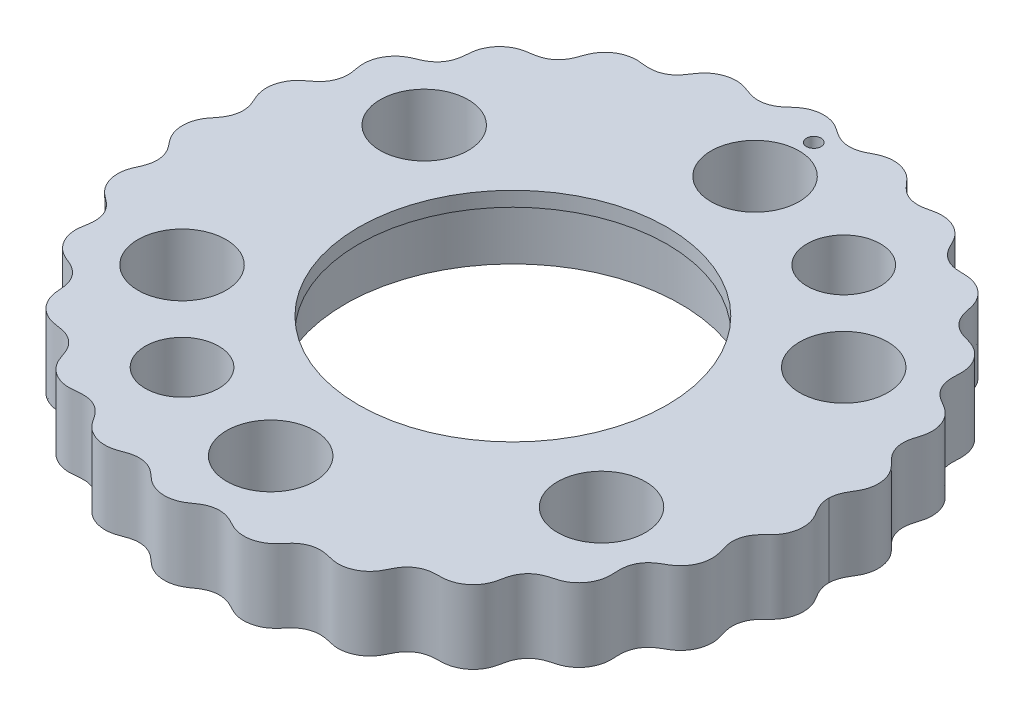
SolidWorks part; units mm, degrees
material "Like ABS"
ref_plane "Front Plane" through (0, 0, 0) normal (0, 0, 1) x (1, 0, 0)
ref_plane "Top Plane" through (0, 0, 0) normal (0, 1, 0) x (1, 0, 0)
ref_plane "Right Plane" through (0, 0, 0) normal (1, 0, 0) x (0, 0, -1)
sketch "Sketch1" plane through (0, 0, 0) normal (0, 1, 0) x (1, 0, 0)
  spline S0 degree 4 poles (18.6029, 11.2545) (18.6075, 11.136) (18.6309, 10.8996) (18.7179, 10.5625) (18.9374, 10.1618) (19.2203, 9.8531) (19.5263, 9.6277) (19.8338, 9.4559) (20.1167, 9.2925) (20.3955, 9.0753) (20.6516, 8.7949) (20.9212, 8.3592) (21.0701, 7.871) (21.0935, 7.3941) (21.0151, 6.9603) (20.9268, 6.6713) (20.827, 6.3532) (20.7583, 5.9932) (20.7579, 5.5953) (20.855, 5.178) (21.0326, 4.8178) (21.2602, 4.5208) (21.5076, 4.2761) (21.7427, 4.0542) (21.9657, 3.7863) (22.1537, 3.4641) (22.3225, 2.9952) (22.3687, 2.5028) (22.3031, 2.0452) (22.1511, 1.6464) (22.0285, 1.4194) (21.9119, 1.2324) (21.8067, 1.0573) (21.7163, 0.8934) (21.6305, 0.703) (21.5677, 0.5145) (21.5301, 0.3455) (21.5114, 0.2182) (21.5031, 0.1178) (21.4994, 0.0196) (21.5, -0.0455) (21.5057, -0.1633) (21.518, -0.2671) (21.5363, -0.3716) (21.5605, -0.4763) (21.5978, -0.6046) (21.6488, -0.7429) (21.7155, -0.8894) (21.7983, -1.0429) (21.8809, -1.1813) (21.9656, -1.3183) (22.0477, -1.4571) (22.1416, -1.6354) (22.2863, -1.9816) (22.3684, -2.421) (22.3358, -2.9349) (22.1741, -3.4197) (21.991, -3.7495) (21.772, -4.0233) (21.539, -4.2475) (21.2876, -4.4904) (21.0523, -4.786) (20.8663, -5.1459) (20.7615, -5.5648) (20.7557, -5.9689) (20.8225, -6.3389) (20.9266, -6.6708) (21.0208, -6.9784) (21.0782, -7.3225) (21.0775, -7.6978) (21.0031, -8.0938) (20.8436, -8.4925) (20.6233, -8.8316) (20.3625, -9.1053) (20.0808, -9.3156) (19.7984, -9.4746) (19.4941, -9.6484) (19.193, -9.8781) (18.9224, -10.185) (18.7166, -10.5727) (18.6147, -10.9677) (18.5925, -11.3426) (18.6115, -11.683) (18.6241, -11.9911) (18.5951, -12.3311) (18.5028, -12.6932) (18.3324, -13.0606) (18.0751, -13.4116) (17.7743, -13.6867) (17.4523, -13.8864) (17.126, -14.0192) (16.8121, -14.1026) (16.4734, -14.1962) (16.1245, -14.3457) (15.7808, -14.582) (15.4788, -14.9208) (15.2835, -15.2936) (15.1749, -15.6637) (15.1113, -15.9998) (15.0432, -16.2929) (14.9273, -16.6033) (14.7486, -16.9176) (14.4956, -17.2208) (14.1638, -17.4903) (13.8066, -17.6794) (13.4438, -17.7919) (13.0938, -17.8383) (12.7683, -17.8404) (12.4162, -17.8477) (12.0403, -17.9075) (11.6491, -18.0533) (11.2738, -18.3086) (10.994, -18.6222) (10.7986, -18.9537) (10.654, -19.2627) (10.5146, -19.5288) (10.3249, -19.7991) (10.0732, -20.058) (9.7528, -20.2872) (9.3635, -20.4656) (8.8909, -20.5765) (8.4239, -20.5773) (8.0011, -20.4727) (7.5788, -20.3726) (7.1982, -20.3396) (6.7831, -20.3853) (6.3568, -20.5422) (6.0096, -20.7778) (5.7397, -21.0508) (5.5235, -21.3136) (5.3222, -21.5355) (5.0709, -21.7488) (4.7631, -21.9354) (4.2941, -22.1159) (3.7831, -22.1727) (3.2971, -22.1042) (2.8667, -21.9331) (2.5797, -21.7766) (2.2654, -21.614) (1.9042, -21.4879) (1.4895, -21.4317) (1.0382, -21.4801) (0.6443, -21.6241) (0.3167, -21.822) (0.0427, -22.0226) (-0.2074, -22.1862) (-0.5976, -22.3746) (-1.0573, -22.4797) (-1.5638, -22.4712) (-2.0548, -22.3329) (-2.3972, -22.1622) (-2.6839, -21.9521) (-2.9229, -21.7281) (-3.1883, -21.4926) (-3.5084, -21.2816) (-3.8975, -21.126) (-4.347, -21.0633) (-4.7636, -21.107) (-5.1287, -21.2185) (-5.4432, -21.3443) (-5.7258, -21.4396) (-6.0477, -21.503) (-6.4056, -21.516) (-6.9028, -21.4457) (-7.3774, -21.2468) (-7.7696, -20.9496) (-8.0632, -20.5887) (-8.2391, -20.3115) (-8.4387, -20.0171) (-8.6983, -19.7336) (-9.0382, -19.4877) (-9.459, -19.3178) (-9.8732, -19.2589) (-10.2536, -19.2774) (-10.5887, -19.3211) (-10.8854, -19.3421) (-11.2121, -19.3225) (-11.5609, -19.2451) (-12.0244, -19.0522) (-12.4339, -18.7404) (-12.7391, -18.3536) (-12.9328, -17.9294) (-13.034, -17.6163) (-13.1553, -17.2811) (-13.3382, -16.9419) (-13.6084, -16.6204) (-13.9753, -16.3534) (-14.3622, -16.1956) (-14.7346, -16.1206) (-15.0692, -16.0797) (-15.3611, -16.0255) (-15.6715, -15.9244) (-15.9889, -15.7621) (-16.3889, -15.4591) (-16.707, -15.0543) (-16.9055, -14.6024) (-16.9861, -14.1422) (-17.0061, -13.8129) (-17.0516, -13.3486) (-17.2053, -12.8653) (-17.5221, -12.4221) (-17.9472, -12.11) (-18.2892, -11.9462) (-18.6023, -11.8239) (-18.8706, -11.6981) (-19.1448, -11.5225) (-19.4105, -11.2862) (-19.7169, -10.8984) (-19.9236, -10.4312) (-20.0056, -9.9443) (-19.9703, -9.4736) (-19.9036, -9.1351) (-19.8344, -8.6685) (-19.87, -8.1618) (-20.0706, -7.6597) (-20.4022, -7.2591) (-20.6929, -7.0172) (-20.9651, -6.8212) (-21.1925, -6.6324) (-21.4131, -6.3939) (-21.6103, -6.0991) (-21.8094, -5.647) (-21.8921, -5.1426) (-21.849, -4.6501) (-21.6959, -4.2025) (-21.5464, -3.8907) (-21.3642, -3.4543) (-21.2752, -2.9536) (-21.3478, -2.4176) (-21.5717, -1.9486) (-21.7936, -1.6436) (-22.008, -1.3867) (-22.1801, -1.1472) (-22.3332, -0.8616) (-22.4495, -0.5273) (-22.5298, -0.0326) (-22.4807, 0.4807) (-22.3113, 0.9462) (-22.0028, 1.4061) (-21.7069, 1.7352) (-21.4589, 2.1409) (-21.3173, 2.6263) (-21.2993, 3.0795) (-21.3816, 3.487) (-21.5215, 3.836) (-21.6648, 4.1376) (-21.7709, 4.412) (-21.8468, 4.7263) (-21.8752, 5.0782) (-21.8287, 5.5771) (-21.6522, 6.0617) (-21.3708, 6.4704) (-20.9554, 6.8384) (-20.5863, 7.0843) (-20.2459, 7.418) (-19.9902, 7.8549) (-19.8626, 8.2901) (-19.8431, 8.7048) (-19.8931, 9.0765) (-19.9566, 9.4036) (-19.99, 9.6951) (-19.9844, 10.0179) (-19.9234, 10.3644) (-19.7778, 10.7686) (-19.5075, 11.197) (-19.1432, 11.548) (-18.707, 11.7881) (-18.2921, 11.9415) (-17.9411, 12.1158) (-17.615, 12.3592) (-17.3407, 12.6771) (-17.1131, 13.113) (-16.9964, 13.6606) (-17.0054, 14.3306) (-16.7364, 15.0616) (-16.2913, 15.5744) (-15.7979, 15.8786) (-15.396, 16.016) (-15.1079, 16.0745) (-14.7772, 16.1149) (-14.408, 16.1828) (-14.0197, 16.33) (-13.6456, 16.5864) (-13.3098, 16.965) (-13.0983, 17.3919) (-12.9786, 17.8186) (-12.7567, 18.327) (-12.3913, 18.8027) (-11.8998, 19.1399) (-11.3468, 19.3098) (-10.9215, 19.3419) (-10.6278, 19.3257) (-10.3528, 19.2899) (-10.0923, 19.2689) (-9.79, 19.2729) (-9.4538, 19.3259) (-9.0826, 19.4637) (-8.6653, 19.7489) (-8.3568, 20.1103) (-8.1354, 20.4932) (-7.7931, 20.9281) (-7.4026, 21.2327) (-6.9296, 21.4377) (-6.4342, 21.5139) (-6.0801, 21.5062) (-5.761, 21.4486) (-5.4799, 21.3585) (-5.1691, 21.234) (-4.8101, 21.1175) (-4.2947, 21.0501) (-3.7627, 21.1476) (-3.3145, 21.3875) (-2.9563, 21.6957) (-2.706, 21.934) (-2.3276, 22.2175) (-1.8725, 22.4102) (-1.3673, 22.487) (-0.8758, 22.437) (-0.5342, 22.3403) (-0.2392, 22.2038) (0.0107, 22.0455) (0.2812, 21.8471) (0.6018, 21.6456) (1.0852, 21.4547) (1.7135, 21.4142) (2.2854, 21.5972) (2.7601, 21.8887) (3.2776, 22.0998) (3.7655, 22.1719) (4.2739, 22.1193) (4.7371, 21.9474) (5.0441, 21.7674) (5.2958, 21.5605) (5.4982, 21.3439) (5.7115, 21.0838) (5.9734, 20.8092) (6.402, 20.5019) (6.9217, 20.3384) (7.4286, 20.3423) (7.8839, 20.4428) (8.2031, 20.5253) (8.6655, 20.5905) (9.1564, 20.541) (9.6395, 20.3632) (10.0511, 20.076) (10.3034, 19.824) (10.4954, 19.5596) (10.637, 19.2985) (10.7794, 18.9927) (10.9663, 18.6617) (11.2365, 18.3428) (11.6043, 18.077) (11.9937, 17.92) (12.3726, 17.8514) (12.7287, 17.8398) (13.0575, 17.8402) (13.5204, 17.7867) (13.9824, 17.6156) (14.4052, 17.3223) (14.7317, 16.9409) (14.9129, 16.6326) (15.0323, 16.3277) (15.1038, 16.0387) (15.1659, 15.7063) (15.2662, 15.3387) (15.4509, 14.9631) (15.7431, 14.6159) (16.0823, 14.3692) (16.4321, 14.2105) (16.7735, 14.1119) (17.0913, 14.0302) (17.5249, 13.8621) (17.9284, 13.5808) (18.2639, 13.1907) (18.4841, 12.7394) (18.5822, 12.3946) (18.621, 12.0687) (18.6175, 11.7703) (18.595, 11.4321) (18.6023, 11.0501) (18.69, 10.6404) (18.8892, 10.2326) (19.1578, 9.9111) (19.4576, 9.6724) (19.7634, 9.4931) (20.0501, 9.335) (20.3381, 9.1271) (20.6059, 8.8542) (20.8888, 8.4298) (21.0532, 7.9505) (21.0949, 7.4807) (21.0358, 7.0511) (20.9572, 6.7626) (20.8511, 6.4397) (20.7645, 6.0666) (20.7498, 5.6474) (20.844, 5.2034) (21.0261, 4.8267) (21.2579, 4.5228) (21.5095, 4.2743) (21.7471, 4.0499) (21.9729, 3.7768) (22.1629, 3.446) (22.3301, 2.9643) (22.3688, 2.459) (22.2909, 1.993) (22.125, 1.5913) (21.9948, 1.3636) (21.8754, 1.1738) (21.7855, 1.0192) (21.7229, 0.9018) (21.6699, 0.7888) (21.6258, 0.6809) (21.5876, 0.571) (21.5558, 0.4582) (21.5339, 0.3595) (21.5196, 0.2744) (21.5104, 0.198) (21.5049, 0.135) (21.5, 0.0567) (21.4996, -0.0017) (21.5018, -0.1012) (21.5095, -0.1957) (21.52, -0.278) (21.5372, -0.3768) (21.5635, -0.4882) (21.5962, -0.5972) (21.6446, -0.7314) (21.7208, -0.903) (21.8329, -1.1074) (21.9824, -1.3413) (22.1279, -1.5977) (22.29, -1.9928) (22.3678, -2.4527) (22.3316, -2.9539) (22.1699, -3.4295) (21.9869, -3.7545) (21.7737, -4.0201) (21.5527, -4.235) (21.3073, -4.4702) (21.0701, -4.7589) (20.8765, -5.1175) (20.7635, -5.5432) (20.754, -5.9559) (20.8209, -6.3344) (20.9276, -6.6735) (21.0237, -6.9882) (21.08, -7.3402) (21.0755, -7.7242) (20.9743, -8.2226) (20.75, -8.681) (20.4407, -9.0464) (20.0199, -9.3618) (19.6438, -9.5512) (19.2696, -9.7988) (18.8657, -10.2421) (18.6796, -10.6464) (18.6183, -10.9774) (18.6053, -11.2049) knots 0 0 0 0 0 0.002701 0.005401 0.007852 0.010303 0.012162 0.01402 0.015879 0.017738 0.020183 0.022628 0.027478 0.029198 0.030919 0.032639 0.034359 0.036796 0.039233 0.041633 0.044032 0.045873 0.047715 0.049556 0.051397 0.053785 0.056173 0.060839 0.062515 0.06419 0.065866 0.066703 0.067541 0.06884 0.070138 0.071436 0.072085 0.072735 0.073159 0.073583 0.074192 0.074801 0.075411 0.07602 0.076629 0.077238 0.078456 0.079374 0.080292 0.08121 0.082128 0.083046 0.083964 0.0858 0.090659 0.093093 0.095528 0.097369 0.09921 0.101051 0.102892 0.105333 0.107775 0.110206 0.112638 0.114469 0.1163 0.118132 0.119963 0.122386 0.12481 0.12725 0.129691 0.131536 0.133381 0.135227 0.137072 0.139519 0.141967 0.144472 0.146978 0.148733 0.150488 0.152242 0.153997 0.156479 0.158961 0.161407 0.163853 0.165702 0.167552 0.169401 0.171251 0.173704 0.176158 0.178823 0.181488 0.183199 0.184911 0.186622 0.188334 0.190723 0.193111 0.195563 0.198015 0.199869 0.201722 0.203576 0.205429 0.207889 0.210349 0.213008 0.215667 0.217374 0.219082 0.220789 0.222496 0.224879 0.227262 0.22972 0.232177 0.235893 0.23775 0.239608 0.242074 0.244541 0.247193 0.249845 0.251549 0.253252 0.254955 0.256659 0.259036 0.261413 0.266339 0.268201 0.270063 0.271925 0.273787 0.276259 0.278732 0.281378 0.284024 0.285723 0.287422 0.289122 0.290821 0.295564 0.298032 0.300501 0.302367 0.304233 0.3061 0.307966 0.310444 0.312923 0.315563 0.318202 0.319898 0.321593 0.323288 0.324983 0.327349 0.329714 0.334663 0.336534 0.338404 0.340274 0.342144 0.344629 0.347114 0.349748 0.352381 0.354072 0.355763 0.357454 0.359146 0.361505 0.363865 0.368826 0.3707 0.372574 0.374449 0.376323 0.378814 0.381305 0.383932 0.386559 0.388246 0.389933 0.391621 0.393308 0.395662 0.398016 0.402988 0.404866 0.406745 0.408623 0.410502 0.415496 0.418117 0.420737 0.42242 0.424103 0.425787 0.42747 0.429818 0.432167 0.436982 0.438947 0.440912 0.442877 0.444842 0.449687 0.452301 0.454914 0.456594 0.458273 0.459953 0.461632 0.463975 0.466317 0.471143 0.473113 0.475082 0.477052 0.479021 0.483878 0.486485 0.489092 0.490767 0.492443 0.494118 0.495794 0.498131 0.500468 0.505475 0.507365 0.509256 0.513038 0.515553 0.518068 0.520669 0.523269 0.524941 0.526613 0.528284 0.529956 0.532287 0.534618 0.539637 0.541532 0.543426 0.547216 0.549737 0.552259 0.554853 0.557447 0.559114 0.560782 0.56245 0.564118 0.566443 0.568769 0.572172 0.575575 0.5778 0.580025 0.58225 0.584475 0.587001 0.589527 0.593322 0.597118 0.602145 0.606799 0.608468 0.610137 0.611805 0.613474 0.61607 0.618666 0.621185 0.623705 0.627493 0.629386 0.63128 0.636295 0.640961 0.642634 0.644306 0.645979 0.647652 0.648953 0.650254 0.652856 0.65537 0.657884 0.661663 0.663553 0.665442 0.670446 0.672784 0.675123 0.676799 0.678476 0.680152 0.681829 0.684438 0.687047 0.6919 0.693868 0.695837 0.697805 0.699773 0.704597 0.706941 0.709285 0.710965 0.712646 0.714326 0.716007 0.718622 0.721238 0.726079 0.730007 0.731971 0.733935 0.738747 0.741097 0.743447 0.745131 0.746815 0.7485 0.750184 0.752806 0.755428 0.760419 0.762297 0.764174 0.766052 0.767929 0.772898 0.775253 0.777609 0.779297 0.780986 0.782674 0.784362 0.786991 0.789619 0.792109 0.794598 0.796471 0.798345 0.800218 0.802091 0.807049 0.80941 0.811771 0.813464 0.815156 0.816848 0.81854 0.821175 0.82381 0.826294 0.828777 0.830646 0.832515 0.834384 0.836253 0.841199 0.843566 0.845934 0.84763 0.849326 0.851022 0.852719 0.85536 0.858001 0.860479 0.862956 0.864821 0.866686 0.868551 0.870415 0.872883 0.87535 0.880096 0.881796 0.883497 0.885197 0.886897 0.889545 0.892193 0.894664 0.897134 0.898995 0.900856 0.902717 0.904578 0.907039 0.909501 0.914258 0.915963 0.917667 0.919371 0.920224 0.921076 0.921739 0.922403 0.923066 0.92373 0.924393 0.925057 0.925389 0.92572 0.926052 0.926384 0.927237 0.927561 0.927886 0.928536 0.929185 0.929835 0.930484 0.931134 0.932433 0.934109 0.935786 0.937463 0.939139 0.943809 0.946282 0.948755 0.950509 0.952263 0.954018 0.955772 0.958256 0.960739 0.963224 0.965709 0.967581 0.969454 0.971326 0.973198 0.975675 0.978152 0.982844 0.984651 0.986458 0.990073 0.992435 0.994797 1 1 1 1 1 construction
  spline S1 degree 4 poles (21.5, 0) (21.5, -0.0228) (21.501, -0.0677) (21.5057, -0.1633) (21.518, -0.2671) (21.5363, -0.3716) (21.5605, -0.4763) (21.5978, -0.6046) (21.6488, -0.7429) (21.7155, -0.8894) (21.7983, -1.0429) (21.8809, -1.1813) (21.9656, -1.3183) (22.0477, -1.4571) (22.1416, -1.6354) (22.2863, -1.9816) (22.3684, -2.421) (22.3358, -2.9349) (22.1741, -3.4197) (21.991, -3.7495) (21.772, -4.0233) (21.539, -4.2475) (21.2876, -4.4904) (21.0523, -4.786) (20.8663, -5.1459) (20.7615, -5.5648) (20.7557, -5.9689) (20.8225, -6.3389) (20.9266, -6.6708) (21.0208, -6.9784) (21.0782, -7.3225) (21.0775, -7.6978) (21.0031, -8.0938) (20.8436, -8.4925) (20.6233, -8.8316) (20.3625, -9.1053) (20.0808, -9.3156) (19.7984, -9.4746) (19.4941, -9.6484) (19.193, -9.8781) (18.9224, -10.185) (18.7166, -10.5727) (18.6147, -10.9677) (18.5925, -11.3426) (18.6115, -11.683) (18.6241, -11.9911) (18.5951, -12.3311) (18.5028, -12.6932) (18.3324, -13.0606) (18.0751, -13.4116) (17.7743, -13.6867) (17.4523, -13.8864) (17.126, -14.0192) (16.8121, -14.1026) (16.4734, -14.1962) (16.1245, -14.3457) (15.7808, -14.582) (15.4788, -14.9208) (15.2835, -15.2936) (15.1749, -15.6637) (15.1113, -15.9998) (15.0432, -16.2929) (14.9273, -16.6033) (14.7486, -16.9176) (14.4956, -17.2208) (14.1638, -17.4903) (13.8066, -17.6794) (13.4438, -17.7919) (13.0938, -17.8383) (12.7683, -17.8404) (12.4162, -17.8477) (12.0403, -17.9075) (11.6491, -18.0533) (11.2738, -18.3086) (10.994, -18.6222) (10.7986, -18.9537) (10.654, -19.2627) (10.5146, -19.5288) (10.3249, -19.7991) (10.0732, -20.058) (9.7528, -20.2872) (9.3635, -20.4656) (8.8909, -20.5765) (8.4239, -20.5773) (8.0011, -20.4727) (7.5788, -20.3726) (7.1982, -20.3396) (6.7831, -20.3853) (6.3568, -20.5422) (6.0096, -20.7778) (5.7397, -21.0508) (5.5235, -21.3136) (5.3222, -21.5355) (5.0709, -21.7488) (4.7631, -21.9354) (4.2941, -22.1159) (3.7831, -22.1727) (3.2971, -22.1042) (2.8667, -21.9331) (2.5797, -21.7766) (2.2654, -21.614) (1.9042, -21.4879) (1.4895, -21.4317) (1.0382, -21.4801) (0.6443, -21.6241) (0.3167, -21.822) (0.0427, -22.0226) (-0.2074, -22.1862) (-0.5976, -22.3746) (-1.0573, -22.4797) (-1.5638, -22.4712) (-2.0548, -22.3329) (-2.3972, -22.1622) (-2.6839, -21.9521) (-2.9229, -21.7281) (-3.1883, -21.4926) (-3.5084, -21.2816) (-3.8975, -21.126) (-4.347, -21.0633) (-4.7636, -21.107) (-5.1287, -21.2185) (-5.4432, -21.3443) (-5.7258, -21.4396) (-6.0477, -21.503) (-6.4056, -21.516) (-6.9028, -21.4457) (-7.3774, -21.2468) (-7.7696, -20.9496) (-8.0632, -20.5887) (-8.2391, -20.3115) (-8.4387, -20.0171) (-8.6983, -19.7336) (-9.0382, -19.4877) (-9.459, -19.3178) (-9.8732, -19.2589) (-10.2536, -19.2774) (-10.5887, -19.3211) (-10.8854, -19.3421) (-11.2121, -19.3225) (-11.5609, -19.2451) (-12.0244, -19.0522) (-12.4339, -18.7404) (-12.7391, -18.3536) (-12.9328, -17.9294) (-13.034, -17.6163) (-13.1553, -17.2811) (-13.3382, -16.9419) (-13.6084, -16.6204) (-13.9753, -16.3534) (-14.3622, -16.1956) (-14.7346, -16.1206) (-15.0692, -16.0797) (-15.3611, -16.0255) (-15.6715, -15.9244) (-15.9889, -15.7621) (-16.3889, -15.4591) (-16.707, -15.0543) (-16.9055, -14.6024) (-16.9861, -14.1422) (-17.0061, -13.8129) (-17.0516, -13.3486) (-17.2053, -12.8653) (-17.5221, -12.4221) (-17.9472, -12.11) (-18.2892, -11.9462) (-18.6023, -11.8239) (-18.8706, -11.6981) (-19.1448, -11.5225) (-19.4105, -11.2862) (-19.7169, -10.8984) (-19.9236, -10.4312) (-20.0056, -9.9443) (-19.9703, -9.4736) (-19.9036, -9.1351) (-19.8344, -8.6685) (-19.87, -8.1618) (-20.0706, -7.6597) (-20.4022, -7.2591) (-20.6929, -7.0172) (-20.9651, -6.8212) (-21.1925, -6.6324) (-21.4131, -6.3939) (-21.6103, -6.0991) (-21.8094, -5.647) (-21.8921, -5.1426) (-21.849, -4.6501) (-21.6959, -4.2025) (-21.5464, -3.8907) (-21.3642, -3.4543) (-21.2752, -2.9536) (-21.3478, -2.4176) (-21.5717, -1.9486) (-21.7936, -1.6436) (-22.008, -1.3867) (-22.1801, -1.1472) (-22.3332, -0.8616) (-22.4495, -0.5273) (-22.5298, -0.0326) (-22.4807, 0.4807) (-22.3113, 0.9462) (-22.0028, 1.4061) (-21.7069, 1.7352) (-21.4589, 2.1409) (-21.3173, 2.6263) (-21.2993, 3.0795) (-21.3816, 3.487) (-21.5215, 3.836) (-21.6648, 4.1376) (-21.7709, 4.412) (-21.8468, 4.7263) (-21.8752, 5.0782) (-21.8287, 5.5771) (-21.6522, 6.0617) (-21.3708, 6.4704) (-20.9554, 6.8384) (-20.5863, 7.0843) (-20.2459, 7.418) (-19.9902, 7.8549) (-19.8626, 8.2901) (-19.8431, 8.7048) (-19.8931, 9.0765) (-19.9566, 9.4036) (-19.99, 9.6951) (-19.9844, 10.0179) (-19.9234, 10.3644) (-19.7778, 10.7686) (-19.5075, 11.197) (-19.1432, 11.548) (-18.707, 11.7881) (-18.2921, 11.9415) (-17.9411, 12.1158) (-17.615, 12.3592) (-17.3407, 12.6771) (-17.1131, 13.113) (-16.9964, 13.6606) (-17.0054, 14.3306) (-16.7364, 15.0616) (-16.2913, 15.5744) (-15.7979, 15.8786) (-15.396, 16.016) (-15.1079, 16.0745) (-14.7772, 16.1149) (-14.408, 16.1828) (-14.0197, 16.33) (-13.6456, 16.5864) (-13.3098, 16.965) (-13.0983, 17.3919) (-12.9786, 17.8186) (-12.7567, 18.327) (-12.3913, 18.8027) (-11.8998, 19.1399) (-11.3468, 19.3098) (-10.9215, 19.3419) (-10.6278, 19.3257) (-10.3528, 19.2899) (-10.0923, 19.2689) (-9.79, 19.2729) (-9.4538, 19.3259) (-9.0826, 19.4637) (-8.6653, 19.7489) (-8.3568, 20.1103) (-8.1354, 20.4932) (-7.7931, 20.9281) (-7.4026, 21.2327) (-6.9296, 21.4377) (-6.4342, 21.5139) (-6.0801, 21.5062) (-5.761, 21.4486) (-5.4799, 21.3585) (-5.1691, 21.234) (-4.8101, 21.1175) (-4.2947, 21.0501) (-3.7627, 21.1476) (-3.3145, 21.3875) (-2.9563, 21.6957) (-2.706, 21.934) (-2.3276, 22.2175) (-1.8725, 22.4102) (-1.3673, 22.487) (-0.8758, 22.437) (-0.5342, 22.3403) (-0.2392, 22.2038) (0.0107, 22.0455) (0.2812, 21.8471) (0.6018, 21.6456) (1.0852, 21.4547) (1.7135, 21.4142) (2.2854, 21.5972) (2.7601, 21.8887) (3.2776, 22.0998) (3.7655, 22.1719) (4.2739, 22.1193) (4.7371, 21.9474) (5.0441, 21.7674) (5.2958, 21.5605) (5.4982, 21.3439) (5.7115, 21.0838) (5.9734, 20.8092) (6.402, 20.5019) (6.9217, 20.3384) (7.4286, 20.3423) (7.8839, 20.4428) (8.2031, 20.5253) (8.6655, 20.5905) (9.1564, 20.541) (9.6395, 20.3632) (10.0511, 20.076) (10.3034, 19.824) (10.4954, 19.5596) (10.637, 19.2985) (10.7794, 18.9927) (10.9663, 18.6617) (11.2365, 18.3428) (11.6043, 18.077) (11.9937, 17.92) (12.3726, 17.8514) (12.7287, 17.8398) (13.0575, 17.8402) (13.5204, 17.7867) (13.9824, 17.6156) (14.4052, 17.3223) (14.7317, 16.9409) (14.9129, 16.6326) (15.0323, 16.3277) (15.1038, 16.0387) (15.1659, 15.7063) (15.2662, 15.3387) (15.4509, 14.9631) (15.7431, 14.6159) (16.0823, 14.3692) (16.4321, 14.2105) (16.7735, 14.1119) (17.0913, 14.0302) (17.5249, 13.8621) (17.9284, 13.5808) (18.2639, 13.1907) (18.4841, 12.7394) (18.5822, 12.3946) (18.621, 12.0687) (18.6175, 11.7703) (18.595, 11.4321) (18.6023, 11.0501) (18.69, 10.6404) (18.8892, 10.2326) (19.1578, 9.9111) (19.4576, 9.6724) (19.7634, 9.4931) (20.0501, 9.335) (20.3381, 9.1271) (20.6059, 8.8542) (20.8888, 8.4298) (21.0532, 7.9505) (21.0949, 7.4807) (21.0358, 7.0511) (20.9572, 6.7626) (20.8511, 6.4397) (20.7645, 6.0666) (20.7498, 5.6474) (20.844, 5.2034) (21.0261, 4.8267) (21.2579, 4.5228) (21.5095, 4.2743) (21.7471, 4.0499) (21.9729, 3.7768) (22.1629, 3.446) (22.3301, 2.9643) (22.3688, 2.459) (22.2909, 1.993) (22.125, 1.5913) (21.9948, 1.3636) (21.8754, 1.1738) (21.7855, 1.0192) (21.7229, 0.9018) (21.6699, 0.7888) (21.6258, 0.6809) (21.5876, 0.571) (21.5558, 0.4582) (21.5339, 0.3595) (21.5196, 0.2744) (21.5104, 0.198) (21.5049, 0.135) (21.5023, 0.0928) (21.5012, 0.0678) (21.5008, 0.0554) knots 0.073583 0.073583 0.073583 0.073583 0.073583 0.074192 0.074801 0.075411 0.07602 0.076629 0.077238 0.078456 0.079374 0.080292 0.08121 0.082128 0.083046 0.083964 0.0858 0.090659 0.093093 0.095528 0.097369 0.09921 0.101051 0.102892 0.105333 0.107775 0.110206 0.112638 0.114469 0.1163 0.118132 0.119963 0.122386 0.12481 0.12725 0.129691 0.131536 0.133381 0.135227 0.137072 0.139519 0.141967 0.144472 0.146978 0.148733 0.150488 0.152242 0.153997 0.156479 0.158961 0.161407 0.163853 0.165702 0.167552 0.169401 0.171251 0.173704 0.176158 0.178823 0.181488 0.183199 0.184911 0.186622 0.188334 0.190723 0.193111 0.195563 0.198015 0.199869 0.201722 0.203576 0.205429 0.207889 0.210349 0.213008 0.215667 0.217374 0.219082 0.220789 0.222496 0.224879 0.227262 0.22972 0.232177 0.235893 0.23775 0.239608 0.242074 0.244541 0.247193 0.249845 0.251549 0.253252 0.254955 0.256659 0.259036 0.261413 0.266339 0.268201 0.270063 0.271925 0.273787 0.276259 0.278732 0.281378 0.284024 0.285723 0.287422 0.289122 0.290821 0.295564 0.298032 0.300501 0.302367 0.304233 0.3061 0.307966 0.310444 0.312923 0.315563 0.318202 0.319898 0.321593 0.323288 0.324983 0.327349 0.329714 0.334663 0.336534 0.338404 0.340274 0.342144 0.344629 0.347114 0.349748 0.352381 0.354072 0.355763 0.357454 0.359146 0.361505 0.363865 0.368826 0.3707 0.372574 0.374449 0.376323 0.378814 0.381305 0.383932 0.386559 0.388246 0.389933 0.391621 0.393308 0.395662 0.398016 0.402988 0.404866 0.406745 0.408623 0.410502 0.415496 0.418117 0.420737 0.42242 0.424103 0.425787 0.42747 0.429818 0.432167 0.436982 0.438947 0.440912 0.442877 0.444842 0.449687 0.452301 0.454914 0.456594 0.458273 0.459953 0.461632 0.463975 0.466317 0.471143 0.473113 0.475082 0.477052 0.479021 0.483878 0.486485 0.489092 0.490767 0.492443 0.494118 0.495794 0.498131 0.500468 0.505475 0.507365 0.509256 0.513038 0.515553 0.518068 0.520669 0.523269 0.524941 0.526613 0.528284 0.529956 0.532287 0.534618 0.539637 0.541532 0.543426 0.547216 0.549737 0.552259 0.554853 0.557447 0.559114 0.560782 0.56245 0.564118 0.566443 0.568769 0.572172 0.575575 0.5778 0.580025 0.58225 0.584475 0.587001 0.589527 0.593322 0.597118 0.602145 0.606799 0.608468 0.610137 0.611805 0.613474 0.61607 0.618666 0.621185 0.623705 0.627493 0.629386 0.63128 0.636295 0.640961 0.642634 0.644306 0.645979 0.647652 0.648953 0.650254 0.652856 0.65537 0.657884 0.661663 0.663553 0.665442 0.670446 0.672784 0.675123 0.676799 0.678476 0.680152 0.681829 0.684438 0.687047 0.6919 0.693868 0.695837 0.697805 0.699773 0.704597 0.706941 0.709285 0.710965 0.712646 0.714326 0.716007 0.718622 0.721238 0.726079 0.730007 0.731971 0.733935 0.738747 0.741097 0.743447 0.745131 0.746815 0.7485 0.750184 0.752806 0.755428 0.760419 0.762297 0.764174 0.766052 0.767929 0.772898 0.775253 0.777609 0.779297 0.780986 0.782674 0.784362 0.786991 0.789619 0.792109 0.794598 0.796471 0.798345 0.800218 0.802091 0.807049 0.80941 0.811771 0.813464 0.815156 0.816848 0.81854 0.821175 0.82381 0.826294 0.828777 0.830646 0.832515 0.834384 0.836253 0.841199 0.843566 0.845934 0.84763 0.849326 0.851022 0.852719 0.85536 0.858001 0.860479 0.862956 0.864821 0.866686 0.868551 0.870415 0.872883 0.87535 0.880096 0.881796 0.883497 0.885197 0.886897 0.889545 0.892193 0.894664 0.897134 0.898995 0.900856 0.902717 0.904578 0.907039 0.909501 0.914258 0.915963 0.917667 0.919371 0.920224 0.921076 0.921739 0.922403 0.923066 0.92373 0.924393 0.925057 0.925389 0.92572 0.926052 0.926384 0.926384 0.926384 0.926384 0.926384
  spline S2 degree 1 poles (21.5008, 0.0554) (21.5, 0) knots 0 0 1 1
extrude "Boss-Extrude1" add sketch "Sketch1" along normal blind 5
sketch "Sketch2" plane through (0, 5, 0) normal (0, 1, 0) x (1, 0, 0)
  circle A0 centre (0, 0) radius 11.425
  dimension "D1" = 22.85
extrude "Cut-Extrude1" cut sketch "Sketch2" against normal up to surface (5 mm away) up to face at (21.5004, 0, -0.0277)
sketch "Sketch3" plane through (0, 5, 0) normal (0, 1, 0) x (1, 0, 0)
  line L0 (0, 0) -> (0, 16.5) construction
  circle A0 centre (0, 16.5) radius 3
  dimension "D1" = 6
  dimension "D2" = 16.5
extrude "Cut-Extrude2" cut sketch "Sketch3" against normal up to surface (5 mm away) up to face at (0, 0, -11.425)
pattern_circular "CirPattern1" count 6 over 360 about axis through (0, 0, 0) along (0, 1, 0) of "Cut-Extrude2"
sketch "Sketch5" plane through (0, 5, 0) normal (0, 1, 0) x (1, 0, 0)
  line L0 (0, 16.5) -> (0, 0) construction
  line L1 (0, 0) -> (8.25, 14.2894) construction
  circle A0 centre (8.25, 14.2894) radius 2.5
  dimension "D2" = 5
  dimension "D1" = 30
extrude "Cut-Extrude3" cut sketch "Sketch5" against normal up to surface (5 mm away) up to face at (-14.2894, 0, -11.25)
pattern_circular "CirPattern2" count 2 over 360 about axis through (0, 0, 0) along (0, 1, 0) of "Cut-Extrude3"
sketch "Sketch6" plane through (0, 5, 0) normal (0, 1, 0) x (1, 0, 0)
  circle A0 centre (0, 0) radius 12.4512
  circle A1 centre (0, 0) radius 10.5
  dimension "D1" = 21
extrude "Boss-Extrude2" add sketch "Sketch6" against normal blind 1
sketch "Sketch7" plane through (0, 5, 0) normal (0, 1, 0) x (1, 0, 0)
  line L2 (0, 0) -> (0, 20.5) construction
  circle A1 centre (0, 20.5) radius 0.5
  dimension "D4" = 1
  dimension "D3" = 20.5
extrude "Cut-Extrude4" cut sketch "Sketch7" against normal up to surface (5 mm away) up to face at (-8.25, 0, 11.7894)
